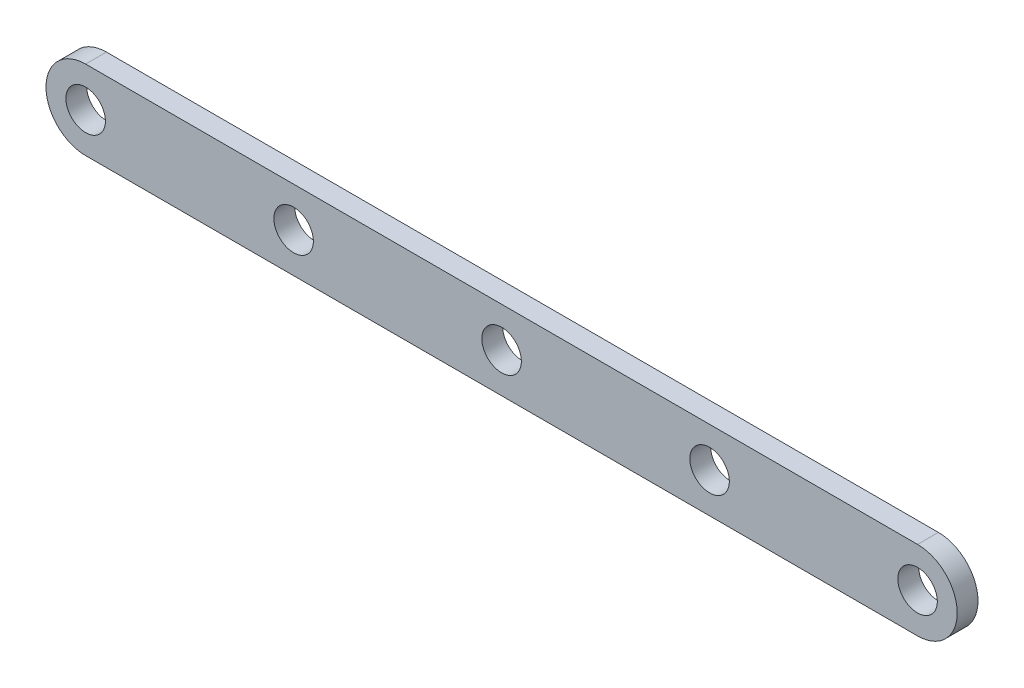
SolidWorks part; units mm, degrees
material "6061 Alloy"
ref_plane "Front Plane" through (0, 0, 0) normal (0, 0, 1) x (1, 0, 0)
ref_plane "Top Plane" through (0, 0, 0) normal (0, 1, 0) x (1, 0, 0)
ref_plane "Right Plane" through (0, 0, 0) normal (1, 0, 0) x (0, 0, -1)
sketch "Croquis1" plane through (0, 0, 0) normal (0, 0, 1) x (1, 0, 0)
  line L1 (76.2, -4.8413) -> (-25.4, -4.8413)
  line L3 (76.2, 4.8413) -> (-25.4, 4.8413)
  arc A0 (-25.4, 4.8413) -> (-25.4, -4.8413) centre (-25.4, 0) ccw
  arc A1 (76.2, -4.8413) -> (76.2, 4.8413) centre (76.2, 0) ccw
  point P0 (0, 0)
  dimension "D1" = 101.6
extrude "Saliente-Extruir3" add sketch "Croquis1" along normal mid plane 2.54
sketch "Croquis4" plane through (0, 0, 1.27) normal (0, 0, 1) x (1, 0, 0)
  circle A0 centre (-25.4, 0) radius 2.413
  dimension "D1" = 4.826
extrude "Cortar-Extruir2" cut sketch "Croquis4" against normal through all
pattern_linear "MatrizL3" count 5 spacing 25.4 along (1, 0, 0) of "Cortar-Extruir2"
